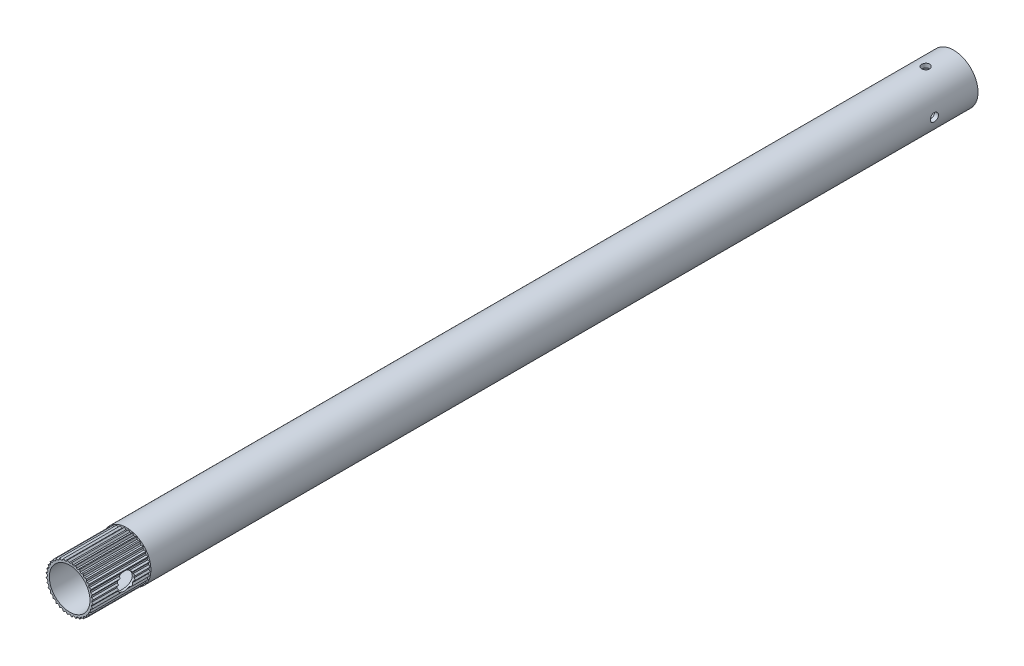
SolidWorks part; units mm, degrees
material "AISI 4130 Steel, normalized at 870C"
ref_plane "X-Y Datum" through (0, 0, 0) normal (0, 0, 1) x (1, 0, 0)
ref_plane "X-Z Datum" through (0, 0, 0) normal (0, 1, 0) x (1, 0, 0)
ref_plane "Y-Z Datum" through (0, 0, 0) normal (1, 0, 0) x (0, 0, -1)
sketch "Sketch9" plane through (0, 0, 0) normal (0, 1, 0) x (1, 0, 0)
  line L0 (16.002, 0) -> (0, 0)
  line L1 (0, 0) -> (0, -389.0916)
  line L2 (0, -389.0916) -> (-72.2493, -524.9728)
  dimension "D1" = 153.895
  dimension "D2" = 28
  dimension "D3" = 389.0916
  dimension "D5" = 16.002
sketch "Sketch5" plane through (0, 0, 0) normal (0, 1, 0) x (1, 0, 0)
  line L0 (7.9375, -367.5016) -> (7.9375, -22.1615)
  line L1 (7.9375, -22.1615) -> (9.525, -22.1615)
  line L2 (9.525, -22.1615) -> (9.525, -367.5016)
  line L3 (9.525, -367.5016) -> (7.9375, -367.5016)
  line L5 (16.002, 0) -> (0, 0) construction
  line L6 (0, 0) -> (0, -389.0916) construction
  line L7 (0, -389.0916) -> (9.525, -389.0916) construction
  line L8 (12.5602, -369.8416) -> (0, -369.8416) construction
  dimension "D1" = 1.5875
  dimension "D2" = 22.1615
  dimension "D3" = 7.9375
  dimension "D4" = 19.25
  dimension "D5" = 21.59
revolve "Revolve2" add sketch "Sketch5" angle 360 about L1
sketch "Sketch6" plane through (0, 0, 0) normal (0, 1, 0) x (1, 0, 0)
  circle A0 centre (0, -33.1635) radius 1.5875 construction
  circle A1 centre (0, -33.1635) radius 1.5875
sketch "Sketch7" plane through (0, 0, 0) normal (1, 0, 0) x (0, 0, -1)
  line L1 (0, 0) -> (-389.0916, 0) construction
  circle A2 centre (-39.196, 0) radius 1.5875
  circle A3 centre (-354.348, 0) radius 3.3782
  circle A4 centre (-39.196, 0) radius 1.5875 construction
  dimension "D2" = 6.7564
  dimension "D1" = 15.4936
extrude "Cut-Extrude5" cut sketch "Sketch7" against normal through all both and the other way through all
extrude "Cut-Extrude6" cut sketch "Sketch6" against normal through all both and the other way through all
sketch "Sketch8" plane through (0, 0, 0) normal (0, 0, 1) x (1, 0, 0)
  line L0 (9.2357, -0.808) -> (8.6817, -0.254)
  line L1 (8.6817, -0.254) -> (8.6817, 0.254)
  line L2 (8.6817, 0.254) -> (9.2357, 0.808)
  line L3 (8.6817, 0) -> (0, 0) construction
  line L4 (8.9551, -2.3995) -> (8.5057, -1.7577)
  line L5 (8.5057, -1.7577) -> (8.5939, -1.2574)
  line L6 (8.5939, -1.2574) -> (9.2357, -0.808)
  line L7 (8.4024, -3.9181) -> (8.0713, -3.208)
  line L8 (8.0713, -3.208) -> (8.245, -2.7306)
  line L9 (8.245, -2.7306) -> (8.9551, -2.3995)
  line L10 (7.5944, -5.3176) -> (7.3916, -4.5608)
  line L11 (7.3916, -4.5608) -> (7.6456, -4.1209)
  line L12 (7.6456, -4.1209) -> (8.4024, -3.9181)
  line L13 (6.5556, -6.5556) -> (6.4873, -5.7751)
  line L14 (6.4873, -5.7751) -> (6.8138, -5.3859)
  line L15 (6.8138, -5.3859) -> (7.5944, -5.3176)
  line L16 (5.3176, -7.5944) -> (5.3859, -6.8138)
  line L17 (5.3859, -6.8138) -> (5.7751, -6.4873)
  line L18 (5.7751, -6.4873) -> (6.5556, -6.5556)
  line L19 (3.9181, -8.4024) -> (4.1209, -7.6456)
  line L20 (4.1209, -7.6456) -> (4.5608, -7.3916)
  line L21 (4.5608, -7.3916) -> (5.3176, -7.5944)
  line L22 (2.3995, -8.9551) -> (2.7306, -8.245)
  line L23 (2.7306, -8.245) -> (3.208, -8.0713)
  line L24 (3.208, -8.0713) -> (3.9181, -8.4024)
  line L25 (0.808, -9.2357) -> (1.2574, -8.5939)
  line L26 (1.2574, -8.5939) -> (1.7577, -8.5057)
  line L27 (1.7577, -8.5057) -> (2.3995, -8.9551)
  line L28 (-0.808, -9.2357) -> (-0.254, -8.6817)
  line L29 (-0.254, -8.6817) -> (0.254, -8.6817)
  line L30 (0.254, -8.6817) -> (0.808, -9.2357)
  line L31 (-2.3995, -8.9551) -> (-1.7577, -8.5057)
  line L32 (-1.7577, -8.5057) -> (-1.2574, -8.5939)
  line L33 (-1.2574, -8.5939) -> (-0.808, -9.2357)
  line L34 (-3.9181, -8.4024) -> (-3.208, -8.0713)
  line L35 (-3.208, -8.0713) -> (-2.7306, -8.245)
  line L36 (-2.7306, -8.245) -> (-2.3995, -8.9551)
  line L37 (-5.3176, -7.5944) -> (-4.5608, -7.3916)
  line L38 (-4.5608, -7.3916) -> (-4.1209, -7.6456)
  line L39 (-4.1209, -7.6456) -> (-3.9181, -8.4024)
  line L40 (-6.5556, -6.5556) -> (-5.7751, -6.4873)
  line L41 (-5.7751, -6.4873) -> (-5.3859, -6.8138)
  line L42 (-5.3859, -6.8138) -> (-5.3176, -7.5944)
  line L43 (-7.5944, -5.3176) -> (-6.8138, -5.3859)
  line L44 (-6.8138, -5.3859) -> (-6.4873, -5.7751)
  line L45 (-6.4873, -5.7751) -> (-6.5556, -6.5556)
  line L46 (-8.4024, -3.9181) -> (-7.6456, -4.1209)
  line L47 (-7.6456, -4.1209) -> (-7.3916, -4.5608)
  line L48 (-7.3916, -4.5608) -> (-7.5944, -5.3176)
  line L49 (-8.9551, -2.3995) -> (-8.245, -2.7306)
  line L50 (-8.245, -2.7306) -> (-8.0713, -3.208)
  line L51 (-8.0713, -3.208) -> (-8.4024, -3.9181)
  line L52 (-9.2357, -0.808) -> (-8.5939, -1.2574)
  line L53 (-8.5939, -1.2574) -> (-8.5057, -1.7577)
  line L54 (-8.5057, -1.7577) -> (-8.9551, -2.3995)
  line L55 (-9.2357, 0.808) -> (-8.6817, 0.254)
  line L56 (-8.6817, 0.254) -> (-8.6817, -0.254)
  line L57 (-8.6817, -0.254) -> (-9.2357, -0.808)
  line L58 (-8.9551, 2.3995) -> (-8.5057, 1.7577)
  line L59 (-8.5057, 1.7577) -> (-8.5939, 1.2574)
  line L60 (-8.5939, 1.2574) -> (-9.2357, 0.808)
  line L61 (-8.4024, 3.9181) -> (-8.0713, 3.208)
  line L62 (-8.0713, 3.208) -> (-8.245, 2.7306)
  line L63 (-8.245, 2.7306) -> (-8.9551, 2.3995)
  line L64 (-7.5944, 5.3176) -> (-7.3916, 4.5608)
  line L65 (-7.3916, 4.5608) -> (-7.6456, 4.1209)
  line L66 (-7.6456, 4.1209) -> (-8.4024, 3.9181)
  line L67 (-6.5556, 6.5556) -> (-6.4873, 5.7751)
  line L68 (-6.4873, 5.7751) -> (-6.8138, 5.3859)
  line L69 (-6.8138, 5.3859) -> (-7.5944, 5.3176)
  line L70 (-5.3176, 7.5944) -> (-5.3859, 6.8138)
  line L71 (-5.3859, 6.8138) -> (-5.7751, 6.4873)
  line L72 (-5.7751, 6.4873) -> (-6.5556, 6.5556)
  line L73 (-3.9181, 8.4024) -> (-4.1209, 7.6456)
  line L74 (-4.1209, 7.6456) -> (-4.5608, 7.3916)
  line L75 (-4.5608, 7.3916) -> (-5.3176, 7.5944)
  line L76 (-2.3995, 8.9551) -> (-2.7306, 8.245)
  line L77 (-2.7306, 8.245) -> (-3.208, 8.0713)
  line L78 (-3.208, 8.0713) -> (-3.9181, 8.4024)
  line L79 (-0.808, 9.2357) -> (-1.2574, 8.5939)
  line L80 (-1.2574, 8.5939) -> (-1.7577, 8.5057)
  line L81 (-1.7577, 8.5057) -> (-2.3995, 8.9551)
  line L82 (0.808, 9.2357) -> (0.254, 8.6817)
  line L83 (0.254, 8.6817) -> (-0.254, 8.6817)
  line L84 (-0.254, 8.6817) -> (-0.808, 9.2357)
  line L85 (2.3995, 8.9551) -> (1.7577, 8.5057)
  line L86 (1.7577, 8.5057) -> (1.2574, 8.5939)
  line L87 (1.2574, 8.5939) -> (0.808, 9.2357)
  line L88 (3.9181, 8.4024) -> (3.208, 8.0713)
  line L89 (3.208, 8.0713) -> (2.7306, 8.245)
  line L90 (2.7306, 8.245) -> (2.3995, 8.9551)
  line L91 (5.3176, 7.5944) -> (4.5608, 7.3916)
  line L92 (4.5608, 7.3916) -> (4.1209, 7.6456)
  line L93 (4.1209, 7.6456) -> (3.9181, 8.4024)
  line L94 (6.5556, 6.5556) -> (5.7751, 6.4873)
  line L95 (5.7751, 6.4873) -> (5.3859, 6.8138)
  line L96 (5.3859, 6.8138) -> (5.3176, 7.5944)
  line L97 (7.5944, 5.3176) -> (6.8138, 5.3859)
  line L98 (6.8138, 5.3859) -> (6.4873, 5.7751)
  line L99 (6.4873, 5.7751) -> (6.5556, 6.5556)
  line L100 (8.4024, 3.9181) -> (7.6456, 4.1209)
  line L101 (7.6456, 4.1209) -> (7.3916, 4.5608)
  line L102 (7.3916, 4.5608) -> (7.5944, 5.3176)
  line L103 (8.9551, 2.3995) -> (8.245, 2.7306)
  line L104 (8.245, 2.7306) -> (8.0713, 3.208)
  line L105 (8.0713, 3.208) -> (8.4024, 3.9181)
  line L106 (9.2357, 0.808) -> (8.5939, 1.2574)
  line L107 (8.5939, 1.2574) -> (8.5057, 1.7577)
  line L108 (8.5057, 1.7577) -> (8.9551, 2.3995)
  circle A0 centre (0, 0) radius 12.7
  circle A1 centre (0, 0) radius 9.271 construction
  circle A2 centre (0, 0) radius 8.6854 construction
  point P153 (0, 0)
  dimension "D1" = 25.4
  dimension "D4" = 18.542
  dimension "D6" = 17.3708
  dimension "D2" = 0.508
  dimension "D3" = 135
  dimension "D5" = 36
extrude "Cut-Extrude7" cut sketch "Sketch8" against normal blind 22.225 from surface at 367.5016 starting at face at (-9.525, 0, 367.5016)
